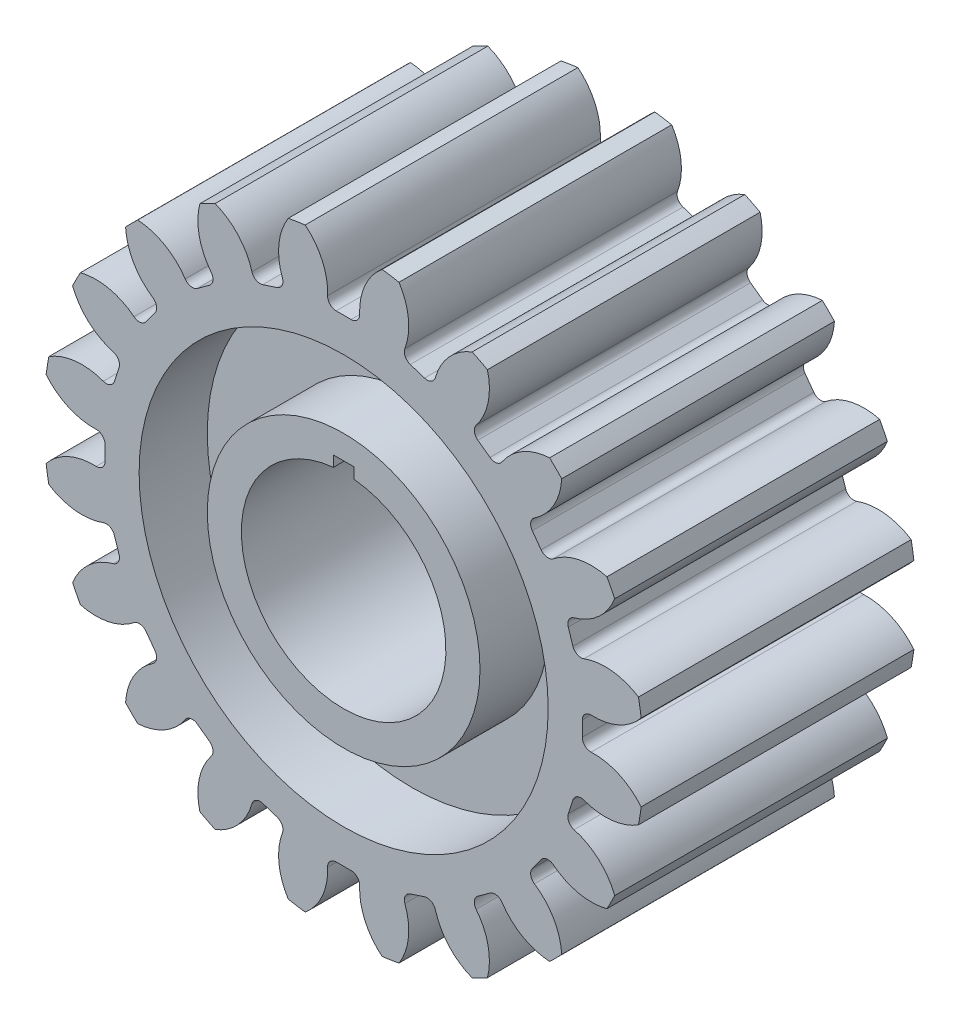
SolidWorks part; units mm, degrees
ref_plane "Front Plane" through (0, 0, 0) normal (0, 0, 1) x (1, 0, 0)
ref_plane "Top Plane" through (0, 0, 0) normal (0, 1, 0) x (1, 0, 0)
ref_plane "Right Plane" through (0, 0, 0) normal (1, 0, 0) x (0, 0, -1)
sketch "Sketch1" plane through (0, 0, 0) normal (0, 0, 1) x (1, 0, 0)
  circle A0 centre (0, 0) radius 22
  dimension "D1" = 44
extrude "Gear Profile" add sketch "Sketch1" along normal mid plane 20
sketch "Sketch2" plane through (0, 0, 10) normal (0, 0, 1) x (1, 0, 0)
  line L0 (-0.5509, 17.5) -> (0.5509, 17.5)
  line L1 (0, 21.2183) -> (0, 22.9123) construction
  arc A1 (1.1754, 18.1508) -> (2.8208, 21.8184) centre (5.6716, 18.3366) cw
  circle A2 centre (0, 0) radius 22 construction
  arc A4 (-1.1754, 18.1508) -> (-2.8208, 21.8184) centre (-5.6716, 18.3366) ccw
  circle A5 centre (0, 0) radius 22
  arc A6 (2.8208, 21.8184) -> (-2.8208, 21.8184) centre (0, 0) ccw
  arc A7 (0.5509, 17.5) -> (1.1754, 18.1508) centre (0.5509, 18.125) ccw
  arc A8 (-1.1754, 18.1508) -> (-0.5509, 17.5) centre (-0.5509, 18.125) ccw
  point P12 (0, 17.5)
  point P15 (1.25, 17.5)
  point P19 (-1.25, 17.5)
  dimension "D1" = 0.625
  dimension "D5" = 4.5
  dimension "D2" = 1.25
  dimension "D3" = 1.5708
  dimension "D4" = 0
extrude "Teeth Profile" cut sketch "Sketch2" against normal through all
pattern_circular "Teeth Circular Pattern" count 20 over 360 about axis through (0, 0, 0) along (0, 0, 1) of "Teeth Profile"
sketch "Sketch3" plane through (0, 0, 10) normal (0, 0, 1) x (1, 0, 0)
  line L2 (-0.75, 7.4624) -> (-0.75, 8.25)
  line L3 (-0.75, 8.25) -> (0.75, 8.25)
  line L4 (0.75, 7.4624) -> (0.75, 8.25)
  arc A0 (-0.75, 7.4624) -> (0.75, 7.4624) centre (0, 0) ccw
  point P3 (0, 7.5)
  dimension "D1" = 15
  dimension "D2" = 1.5
extrude "Gear Bore" cut sketch "Sketch3" against normal through all
sketch "Sketch4" plane through (0, 0, 10) normal (0, 0, 1) x (1, 0, 0)
  circle A0 centre (0, 0) radius 10
  circle A1 centre (0, 0) radius 15
  dimension "D1" = 20
  dimension "D2" = 30
extrude "Weight reduction pocket 1" cut sketch "Sketch4" against normal blind 5
mirror "Weight reduction pocket 2" about plane through (0, 0, 0) normal (0, 0, 1) of "Weight reduction pocket 1"
